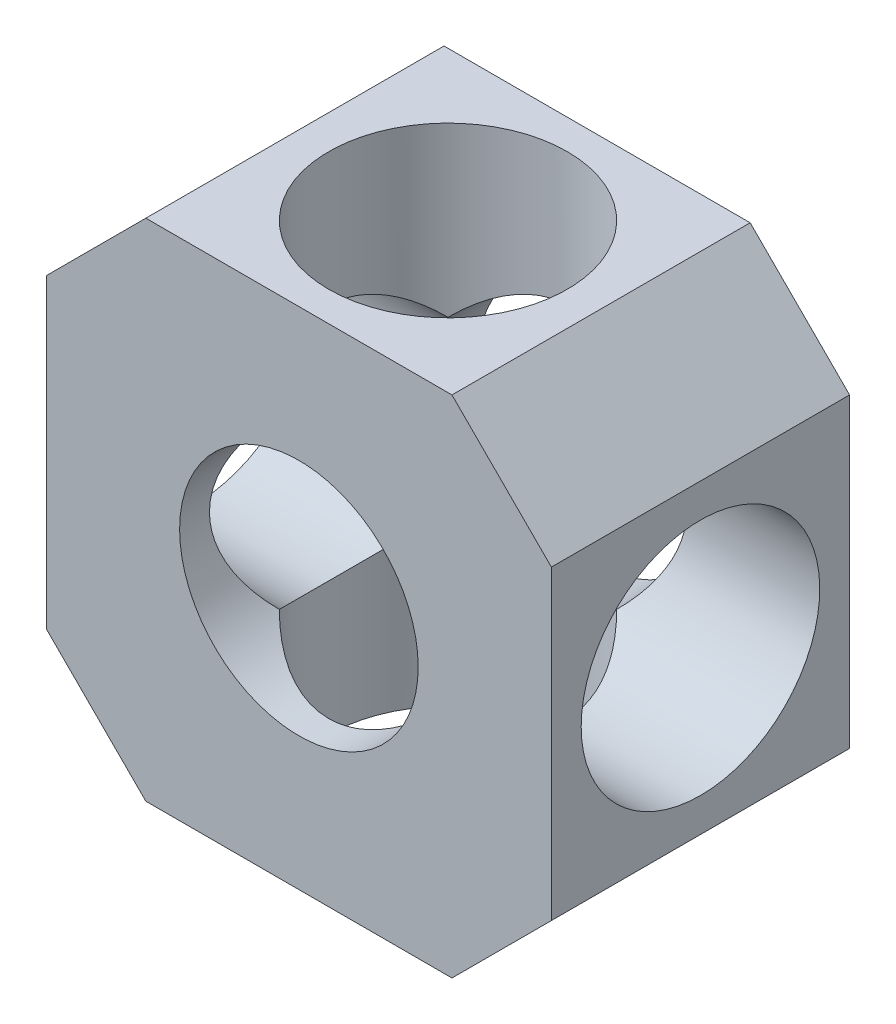
SolidWorks part; units mm, degrees
material "AISI 1020"
ref_plane "Ön Düzlem" through (0, 0, 0) normal (0, 0, 1) x (1, 0, 0)
ref_plane "Üst Düzlem" through (0, 0, 0) normal (0, 1, 0) x (1, 0, 0)
ref_plane "Sağ Düzlem" through (0, 0, 0) normal (1, 0, 0) x (0, 0, -1)
sketch "Çizim2" plane through (0, 0, 0) normal (0, 0, 1) x (1, 0, 0)
  line L1 (-12.7, -12.7) -> (12.7, -12.7)
  line L2 (-12.7, -12.7) -> (-12.7, 12.7)
  line L3 (-12.7, 12.7) -> (12.7, 12.7)
  line L4 (12.7, -12.7) -> (12.7, 12.7)
  line L5 (-12.7, -12.7) -> (12.7, 12.7) construction
  line L6 (-12.7, 12.7) -> (12.7, -12.7) construction
  point P0 (0, 0)
  dimension "D1" = 25.4
  dimension "D2" = 25.4
extrude "Yükseklik-Ekstrüzyon1" add sketch "Çizim2" along normal mid plane 15
chamfer "Pah1" distance 5 angle 45 4 edges at (-12.7, -12.7, 0) (-12.7, 12.7, 0) (12.7, -12.7, 0) (12.7, 12.7, 0)
sketch "Çizim3" plane through (0, 0, -7.5) normal (0, 0, -1) x (-1, 0, 0)
  circle A0 centre (0, 0) radius 6
  dimension "D1" = 12
extrude "Kes-Ekstrüzyon1" cut sketch "Çizim3" against normal blind 15
sketch "Çizim4" plane through (0, 12.7, 0) normal (0, 1, 0) x (1, 0, 0)
  circle A0 centre (0, 0) radius 6
  dimension "D1" = 12
extrude "Kes-Ekstrüzyon3" cut sketch "Çizim4" against normal blind 28
pattern_circular "Dairesel Kaplama1" count 4 every 90 about axis through (0, 0, 7.5) along (0, 0, -1) of "Kes-Ekstrüzyon3"
